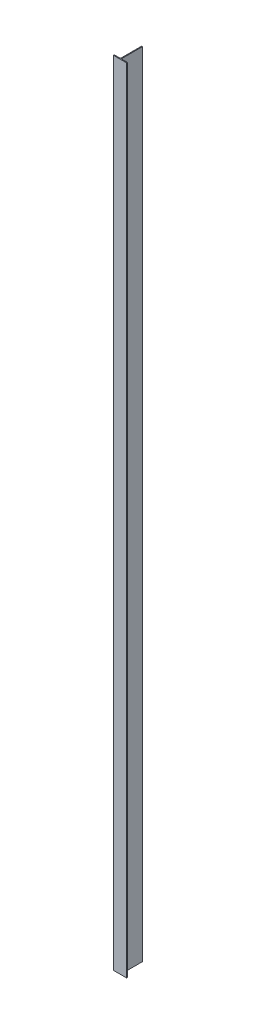
SolidWorks part; units mm, degrees
ref_plane "Front Plane" through (0, 0, 0) normal (0, 0, 1) x (1, 0, 0)
ref_plane "Top Plane" through (0, 0, 0) normal (0, 1, 0) x (1, 0, 0)
ref_plane "Right Plane" through (0, 0, 0) normal (1, 0, 0) x (0, 0, -1)
other "Configuration Table"
sketch "Sketch1" plane through (0, 0, 0) normal (0, 1, 0) x (1, 0, 0)
  line L0 (690, -40) -> (690, -38.5)
  line L1 (690, -38.5) -> (701.25, -38.5)
  line L2 (701.25, -38.5) -> (701.25, 0)
  line L3 (701.25, 0) -> (702.75, 0)
  line L4 (702.75, 0) -> (702.75, -38.5)
  line L5 (702.75, -38.5) -> (714, -38.5)
  line L6 (714, -38.5) -> (714, -40)
  line L7 (714, -40) -> (690, -40)
extrude "STORE_sove_orta_1" add sketch "Sketch1" along normal blind 1427.5 from offset 182.5 separate body
